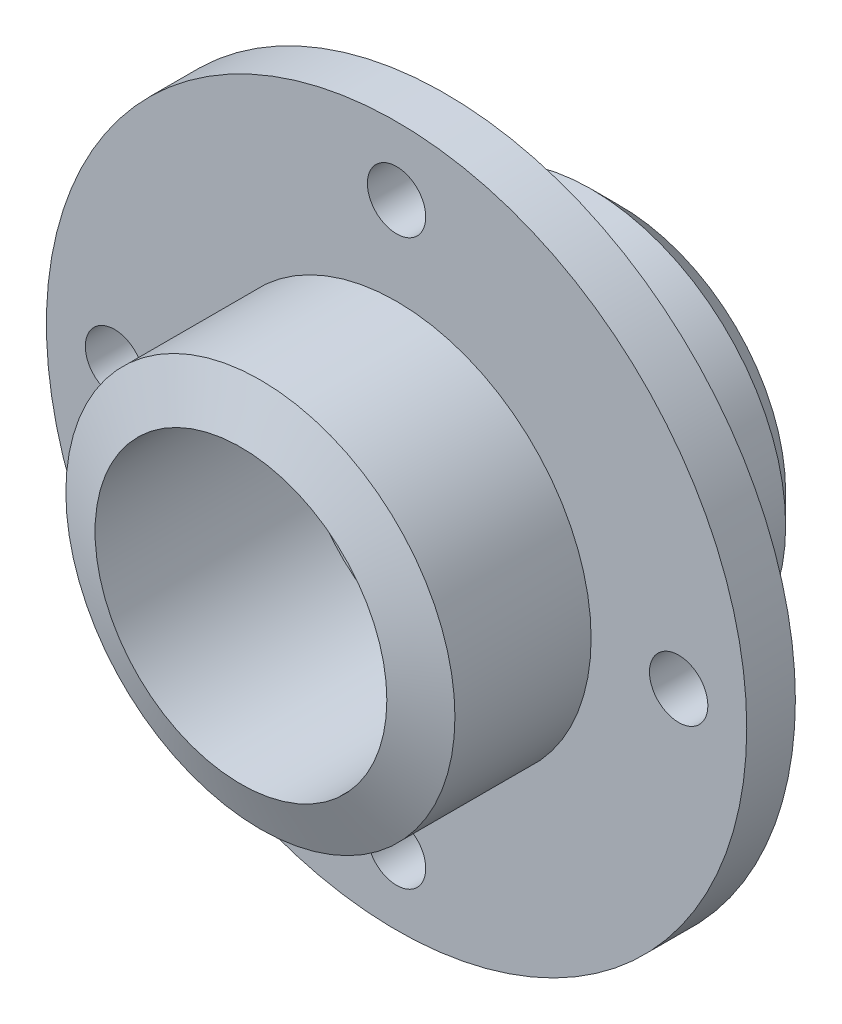
SolidWorks part; units mm, degrees
ref_plane "Front Plane" through (0, 0, 0) normal (0, 0, 1) x (1, 0, 0)
ref_plane "Top Plane" through (0, 0, 0) normal (0, 1, 0) x (1, 0, 0)
ref_plane "Right Plane" through (0, 0, 0) normal (1, 0, 0) x (0, 0, -1)
sketch "Sketch1" plane through (0, 0, 0) normal (0, 1, 0) x (1, 0, 0)
  line L0 (24, 78) -> (24, 72)
  line L1 (24, 72) -> (34, 72)
  line L2 (34, 72) -> (34, 42)
  line L3 (34, 42) -> (30, 42)
  line L4 (30, 42) -> (30, 0)
  line L5 (30, 0) -> (40, 4)
  line L6 (40, 4) -> (40, 32)
  line L7 (40, 32) -> (72, 32)
  line L8 (72, 32) -> (72, 42)
  line L9 (72, 42) -> (40, 42)
  line L10 (40, 42) -> (40, 72)
  line L11 (40, 72) -> (34, 78)
  line L12 (34, 78) -> (24, 78)
  line L13 (0, 0) -> (0, 71.2513) construction
  dimension "D1" = 10
  dimension "D2" = 36
  dimension "D3" = 32
  dimension "D4" = 4
  dimension "D5" = 6
  dimension "D6" = 34
  dimension "D7" = 30
  dimension "D8" = 40
  dimension "D9" = 72
  dimension "D10" = 24
revolve "Revolve1" add sketch "Sketch1" angle 360 about L13
sketch "Sketch2" plane through (0, 0, -42) normal (0, 0, -1) x (-1, 0, 0)
  circle A0 centre (0, 0) radius 58 construction
  circle A1 centre (0, 58) radius 6
  circle A2 centre (58, 0) radius 6
  circle A3 centre (0, -58) radius 6
  circle A4 centre (-58, 0) radius 6
  point P5 (0, 0)
  point P6 (0, 0)
  point P14 (0, 0)
  dimension "D1" = 116
  dimension "D2" = 12
  dimension "D3" = 4
extrude "Cut-Extrude1" cut sketch "Sketch2" against normal through all both
